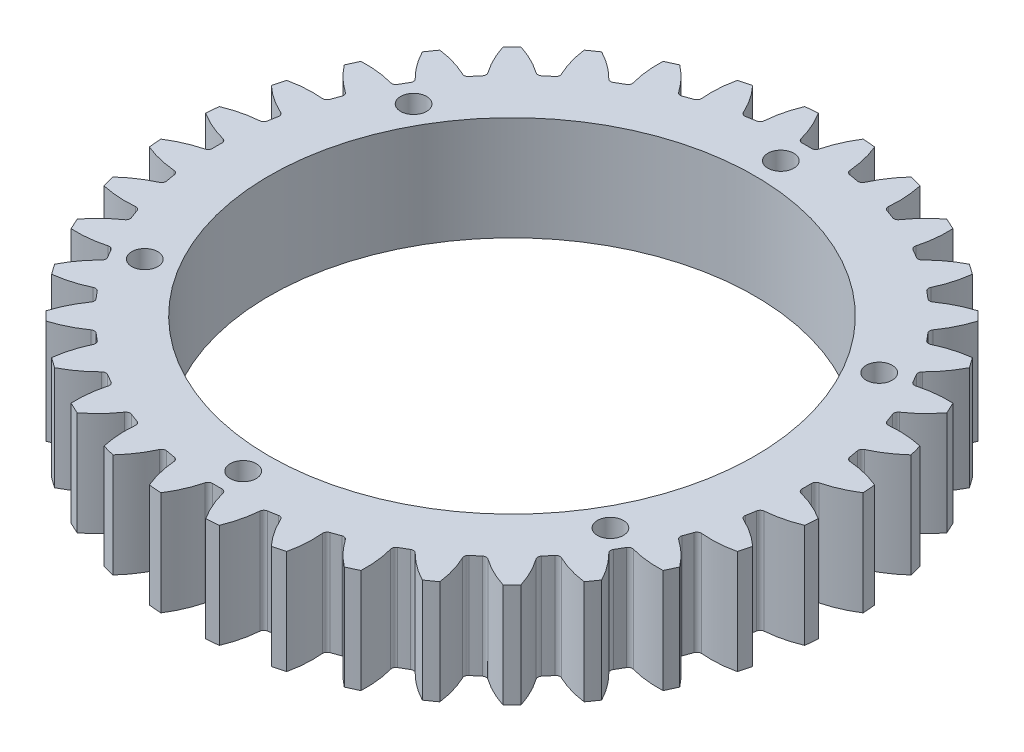
SolidWorks part; units mm, degrees
material "聚脂树脂"
ref_plane "前视基准面" through (0, 0, 0) normal (0, 0, 1) x (1, 0, 0)
ref_plane "上视基准面" through (0, 0, 0) normal (0, 1, 0) x (1, 0, 0)
ref_plane "右视基准面" through (0, 0, 0) normal (1, 0, 0) x (0, 0, -1)
other "Configuration Table"
sketch "草图1" plane through (0, 0, 0) normal (0, 1, 0) x (1, 0, 0)
  line L0 (0, 47.2508) -> (0, -53.1693) construction
  circle A0 centre (0, 0) radius 28
  circle A1 centre (0, 0) radius 38
  circle A2 centre (0, 0) radius 34 construction
  circle A3 centre (0, 0) radius 31 construction
  circle A4 centre (0, 31) radius 1.5
  circle A5 centre (26.8468, 15.5) radius 1.5
  circle A6 centre (26.8468, -15.5) radius 1.5
  circle A7 centre (0, -31) radius 1.5
  circle A8 centre (-26.8468, -15.5) radius 1.5
  circle A9 centre (-26.8468, 15.5) radius 1.5
  point P23 (0, 0)
  dimension "D1" = 56
  dimension "D2" = 76
  dimension "D3" = 68
  dimension "D4" = 62
  dimension "D5" = 3
  dimension "D6" = 6
extrude "凸台-拉伸1" add sketch "草图1" along normal blind 12
sketch "草图2" plane through (0, 0, 0) normal (0, 1, 0) x (1, 0, 0)
  line L0 (0, -46.0485) -> (0, 53.1455) construction
  line L1 (0, 0) -> (2.3204, 53.1454) construction
  line L2 (1.5703, 35.9657) -> (53.5834, 33.6948) construction
  line L3 (1.5703, 35.9657) -> (42.3444, 19.0765) construction
  line L4 (0, 0) -> (12.9458, 31.2539) construction
  circle A0 centre (0, 0) radius 38 construction
  circle A1 centre (0, 0) radius 38 construction
  circle A2 centre (0, 0) radius 36 construction
  arc A3 (2.5884, 37.9117) -> (-2.5884, 37.9117) centre (0, 0) ccw
  arc A4 (2.5884, 37.9117) -> (1.0337, 34.3691) centre (12.9458, 31.2539) ccw
  arc A5 (0.542, 33.9957) -> (-0.542, 33.9957) centre (0, 0) ccw
  arc A6 (1.0337, 34.3691) -> (0.542, 33.9957) centre (0.5499, 34.4956) cw
  arc A7 (-1.0337, 34.3691) -> (-0.542, 33.9957) centre (-0.5499, 34.4956) ccw
  arc A8 (-2.5884, 37.9117) -> (-1.0337, 34.3691) centre (-12.9458, 31.2539) cw
  point P17 (1.5703, 35.9657)
  dimension "D2" = 72
  dimension "D3" = 20
  dimension "D4" = 34
  dimension "D5" = 0.5
  dimension "D1" = 2.5
extrude "切除-拉伸1" cut sketch "草图2" along normal through all
pattern_circular "阵列(圆周)1" count 36 over 360 about axis through (0, 0, 0) along (0, 1, 0) of "切除-拉伸1"
sketch "草图3" plane through (0, 0, 0) normal (0, 1, 0) x (1, 0, 0)
  circle A0 centre (0, 0) radius 36 construction
  dimension "D1" = 72
